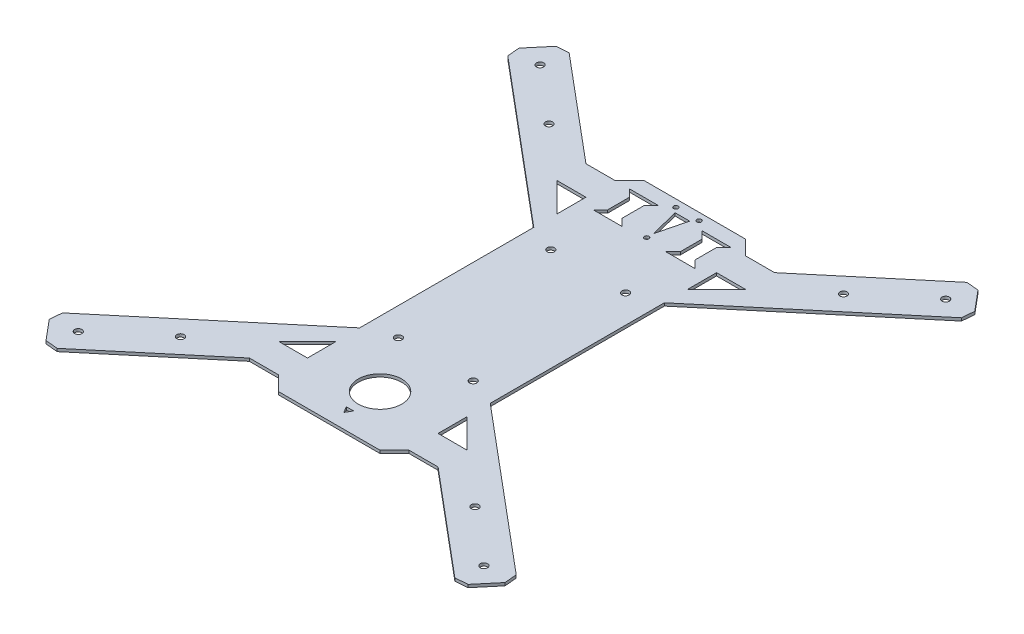
SolidWorks part; units mm, degrees
material "Thornel Mat VMA"
ref_plane "Ön Düzlem" through (0, 0, 0) normal (0, 0, 1) x (1, 0, 0)
ref_plane "Üst Düzlem" through (0, 0, 0) normal (0, 1, 0) x (1, 0, 0)
ref_plane "Sağ Düzlem" through (0, 0, 0) normal (1, 0, 0) x (0, 0, -1)
sketch "Çizim2" plane through (0, 0, 0) normal (0, 1, 0) x (1, 0, 0)
  line L0 (-45, 60) -> (-160.8881, 157.2416)
  line L1 (-45, 100) -> (45, 100)
  line L2 (-45, 100) -> (-45, -100)
  line L3 (-45, -100) -> (45, -100)
  line L4 (45, 100) -> (45, -100)
  line L5 (-160.8881, 157.2416) -> (-141.6044, 180.223)
  line L6 (-141.6044, 180.223) -> (-65, 115.9442)
  line L7 (-65, 115.9442) -> (-45, 115.9442)
  line L8 (-45, 115.9442) -> (-35, 125.9442)
  line L9 (-35, 125.9442) -> (35, 125.9442)
  line L10 (35, 125.9442) -> (45, 115.9442)
  line L11 (45, 115.9442) -> (65, 115.9442)
  line L12 (65, 115.9442) -> (141.6044, 180.223)
  line L13 (141.6044, 180.223) -> (160.8881, 157.2416)
  line L14 (160.8881, 157.2416) -> (45, 60)
  line L15 (0, 0) -> (-44.0753, 0) construction
  line L16 (160.8881, -157.2416) -> (45, -60)
  line L17 (141.6044, -180.223) -> (160.8881, -157.2416)
  line L18 (65, -115.9442) -> (141.6044, -180.223)
  line L19 (45, -115.9442) -> (65, -115.9442)
  line L20 (35, -125.9442) -> (45, -115.9442)
  line L21 (-35, -125.9442) -> (35, -125.9442)
  line L22 (-45, -115.9442) -> (-35, -125.9442)
  line L23 (-65, -115.9442) -> (-45, -115.9442)
  line L24 (-141.6044, -180.223) -> (-65, -115.9442)
  line L25 (-160.8881, -157.2416) -> (-141.6044, -180.223)
  line L26 (-45, -60) -> (-160.8881, -157.2416)
  dimension "D1" = 200
  dimension "D2" = 90
  dimension "D3" = 130
  dimension "D4" = 130
  dimension "D5" = 30
  dimension "D6" = 100
  dimension "D7" = 100
  dimension "D8" = 45
  dimension "D9" = 100
  dimension "D10" = 130
  dimension "D11" = 135
  dimension "D12" = 135
  dimension "D13" = 10
  dimension "D14" = 40
  dimension "D15" = 40
extrude "Yükseklik-Ekstrüzyon2" add sketch "Çizim2" along normal blind 2
sketch "Çizim4" plane through (0, 2, 0) normal (0, 1, 0) x (1, 0, 0)
  line L0 (-2.5, -111.6141) -> (0, -115.9442)
  line L1 (0, -115.9442) -> (2.5, -111.6141)
  line L2 (2.5, -111.6141) -> (-2.5, -111.6141)
  line L3 (-35, -125.9442) -> (35, -125.9442) construction
  dimension "D1" = 5
  dimension "D2" = 5
  dimension "D3" = 5
  dimension "D4" = 10
extrude "Kes-Ekstrüzyon2" cut sketch "Çizim4" against normal up to vertex (2 mm away) up to point (0, 0, 0)
sketch "Çizim5" plane through (0, 2, 0) normal (0, 1, 0) x (1, 0, 0)
  line L0 (-65, 95.9442) -> (-45, 95.9442)
  line L1 (-45, 95.9442) -> (-45, 75.9442)
  line L2 (-45, 75.9442) -> (-65, 95.9442)
  line L3 (-65, 115.9442) -> (-45, 115.9442) construction
  line L4 (0, 0) -> (0, 125.9442) construction
  line L5 (-35, 125.9442) -> (35, 125.9442) construction
  line L6 (0, 0) -> (-45, 0) construction
  line L7 (-45, 60) -> (-45, -60) construction
  line L8 (45, 75.9442) -> (65, 95.9442)
  line L9 (45, 95.9442) -> (45, 75.9442)
  line L10 (65, 95.9442) -> (45, 95.9442)
  line L11 (65, -95.9442) -> (45, -95.9442)
  line L12 (45, -95.9442) -> (45, -75.9442)
  line L13 (45, -75.9442) -> (65, -95.9442)
  line L14 (-45, -75.9442) -> (-65, -95.9442)
  line L15 (-45, -95.9442) -> (-45, -75.9442)
  line L16 (-65, -95.9442) -> (-45, -95.9442)
  dimension "D1" = 20
  dimension "D2" = 20
  dimension "D3" = 20
  dimension "D4" = 45
extrude "Kes-Ekstrüzyon3" cut sketch "Çizim5" against normal blind 20
chamfer "Pah1" distance 6 angle 45 8 edges at (160.8881, 1, -157.2416) (141.6044, 1, -180.223) (-141.6044, 1, -180.223) (-160.8881, 1, -157.2416) (-160.8881, 1, 157.2416) (-141.6044, 1, 180.223) (160.8881, 1, 157.2416) (141.6044, 1, 180.223)
sketch "Çizim6" plane through (0, 2, 0) normal (0, 1, 0) x (1, 0, 0)
  line L0 (-157.0313, 161.8379) -> (-145.4612, 175.6267) construction
  line L1 (-45, 60) -> (-156.2918, 153.3849) construction
  line L2 (0, 0) -> (0, 125.9442) construction
  line L3 (-35, 125.9442) -> (35, 125.9442) construction
  line L4 (0, 0) -> (-45, 0) construction
  line L5 (-45, 60) -> (-45, -60) construction
  line L6 (65, 115.9442) -> (137.0082, 176.3662) construction
  line L7 (145.4612, 175.6267) -> (157.0313, 161.8379) construction
  line L8 (65, -115.9442) -> (137.0082, -176.3662) construction
  line L9 (145.4612, -175.6267) -> (157.0313, -161.8379) construction
  line L10 (-45, -60) -> (-156.2918, -153.3849) construction
  line L11 (-157.0313, -161.8379) -> (-145.4612, -175.6267) construction
  circle A0 centre (-139.7556, 159.0905) radius 2.5
  circle A1 centre (-101.4534, 126.9511) radius 2.5
  circle A8 centre (101.4534, 126.9511) radius 2.5
  circle A9 centre (139.7556, 159.0905) radius 2.5
  circle A10 centre (101.4534, -126.9511) radius 2.5
  circle A11 centre (139.7556, -159.0905) radius 2.5
  circle A12 centre (-101.4534, -126.9511) radius 2.5
  circle A13 centre (-139.7556, -159.0905) radius 2.5
  dimension "D1" = 5
  dimension "D2" = 5
  dimension "D3" = 15
  dimension "D4" = 50
  dimension "D5" = 15
  dimension "D6" = 15
  dimension "D7" = 50
  dimension "D8" = 15
  dimension "D9" = 15
  dimension "D10" = 15
  dimension "D11" = 5
  dimension "D12" = 5
  dimension "D13" = 50
  dimension "D14" = 5
  dimension "D15" = 5
  dimension "D16" = 15
  dimension "D17" = 15
  dimension "D19" = 5
  dimension "D20" = 5
  dimension "D23" = 15
  dimension "D24" = 50
  dimension "D18" = 15
  dimension "D21" = 15
  dimension "D22" = 15
extrude "Kes-Ekstrüzyon4" cut sketch "Çizim6" against normal blind 20
sketch "Çizim7" plane through (0, 2, 0) normal (0, 1, 0) x (1, 0, 0)
  line L0 (-35, 125.9442) -> (35, 125.9442) construction
  line L1 (0, 92.7805) -> (-8, 121.6942) construction
  circle A0 centre (-8, 120.9442) radius 1.55
  circle A1 centre (8, 120.9442) radius 1.55
  circle A2 centre (0, 92.7805) radius 1.55
  dimension "D1" = 3.1
  dimension "D2" = 16
  dimension "D4" = 3.1
  dimension "D5" = 3.1
  dimension "D3" = 0.75
  dimension "D6" = 8
  dimension "D7" = 5
  dimension "D8" = 30
extrude "Kes-Ekstrüzyon5" cut sketch "Çizim7" against normal blind 10
sketch "Çizim8" plane through (0, 2, 0) normal (0, 1, 0) x (1, 0, 0)
  line L0 (-35, -125.9442) -> (35, -125.9442) construction
  circle A0 centre (0, -90.9442) radius 15
  dimension "D1" = 30
  dimension "D2" = 35
extrude "Kes-Ekstrüzyon6" cut sketch "Çizim8" against normal up to vertex (2 mm away) up to point (0, 0, 0)
sketch "Çizim9" plane through (0, 2, 0) normal (0, 1, 0) x (1, 0, 0)
  line L0 (-35, 115.9442) -> (-15, 115.9442)
  line L1 (-15, 115.9442) -> (-20, 110.9442)
  line L2 (-20, 110.9442) -> (-20, 95.9442)
  line L3 (-20, 95.9442) -> (-15, 90.9442)
  line L4 (-15, 90.9442) -> (-35, 90.9442)
  line L5 (-35, 90.9442) -> (-30, 95.9442)
  line L6 (-30, 95.9442) -> (-30, 110.9442)
  line L7 (-30, 110.9442) -> (-35, 115.9442)
  line L8 (-35, 125.9442) -> (35, 125.9442) construction
  line L9 (0, 92.7805) -> (0, 125.9442) construction
  line L10 (30, 110.9442) -> (35, 115.9442)
  line L11 (30, 95.9442) -> (30, 110.9442)
  line L12 (35, 90.9442) -> (30, 95.9442)
  line L13 (15, 90.9442) -> (35, 90.9442)
  line L14 (20, 95.9442) -> (15, 90.9442)
  line L15 (20, 110.9442) -> (20, 95.9442)
  line L16 (15, 115.9442) -> (20, 110.9442)
  line L17 (35, 115.9442) -> (15, 115.9442)
  circle A0 centre (0, 92.7805) radius 1.55 construction
  dimension "D8" = 20
  dimension "D1" = 15
  dimension "D2" = 15
  dimension "D3" = 45
  dimension "D4" = 45
  dimension "D5" = 25
  dimension "D6" = 20
  dimension "D7" = 20
  dimension "D9" = 10
  dimension "D10" = 5
  dimension "D11" = 5
extrude "Kes-Ekstrüzyon7" cut sketch "Çizim9" against normal blind 10
sketch "Çizim10" plane through (0, 2, 0) normal (0, 1, 0) x (1, 0, 0)
  line L0 (-5, 117.4136) -> (0, 97.4136)
  line L1 (0, 97.4136) -> (5, 117.4136)
  line L2 (5, 117.4136) -> (-5, 117.4136)
  line L3 (-8, 120.9442) -> (-5, 117.4136) construction
  line L4 (5, 117.4136) -> (8, 120.9442) construction
  line L5 (0, 92.7805) -> (0, 97.4136) construction
  dimension "D1" = 10
  dimension "D2" = 20
extrude "Kes-Ekstrüzyon8" cut sketch "Çizim10" against normal blind 10
sketch "Çizim11" plane through (0, 2, 0) normal (0, 1, 0) x (1, 0, 0)
  line L0 (0, 0) -> (0, 125.9442) construction
  line L1 (-35, 125.9442) -> (35, 125.9442) construction
  line L2 (0, 0) -> (-45, 0) construction
  line L3 (-45, 60) -> (-45, -60) construction
  circle A0 centre (25.75, -52.5) radius 2.5
  circle A1 centre (-25.75, -52.5) radius 2.5
  circle A2 centre (-25.75, 52.5) radius 2.5
  circle A3 centre (25.75, 52.5) radius 2.5
  dimension "D1" = 5
  dimension "D2" = 19.25
  dimension "D3" = 7.5
extrude "Kes-Ekstrüzyon9" cut sketch "Çizim11" against normal blind 10
